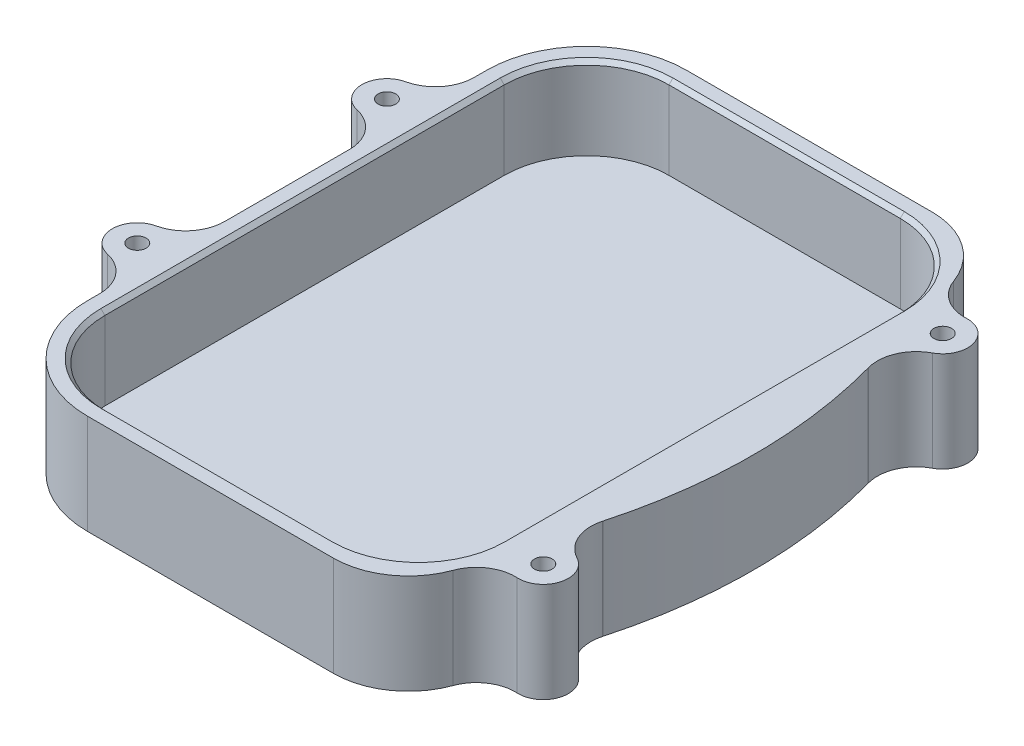
SolidWorks part; units mm, degrees
ref_plane "Front Plane" through (0, 0, 0) normal (0, 0, 1) x (1, 0, 0)
ref_plane "Top Plane" through (0, 0, 0) normal (0, 1, 0) x (1, 0, 0)
ref_plane "Right Plane" through (0, 0, 0) normal (1, 0, 0) x (0, 0, -1)
sketch "Sketch1" plane through (0, 0, 0) normal (0, 1, 0) x (1, 0, 0)
  line L1 (-68.58, 76.2) -> (68.58, 76.2)
  line L2 (-68.58, 76.2) -> (-68.58, -76.2)
  line L3 (-68.58, -76.2) -> (68.58, -76.2)
  line L4 (68.58, 76.2) -> (68.58, -76.2)
  line L5 (-68.58, 76.2) -> (68.58, -76.2) construction
  line L6 (-68.58, -76.2) -> (68.58, 76.2) construction
  point P0 (0, 0)
  dimension "D1" = 137.16
  dimension "D2" = 152.4
extrude "Boss-Extrude2" add sketch "Sketch1" against normal blind 25.4
sketch "Sketch2" plane through (0, 0, 0) normal (0, 1, 0) x (1, 0, 0)
  line L0 (61.1717, -50.8) -> (61.1717, 50.8) construction
  line L1 (-61.1717, 31.75) -> (-61.1717, -31.75) construction
  line L2 (-61.1717, 0) -> (61.1717, 0) construction
  circle A0 centre (-61.1717, 31.75) radius 2.2479
  circle A1 centre (-61.1717, -31.75) radius 2.2479
  circle A2 centre (61.1717, 50.8) radius 2.2479
  circle A3 centre (61.1717, -50.8) radius 2.2479
  point P8 (61.1717, 0)
  point P11 (0, 0)
  dimension "D2" = 4.4958
  dimension "D1" = 122.3433
  dimension "D3" = 101.6
  dimension "D4" = 63.5
sketch "Sketch3" plane through (0, 0, 0) normal (0, 1, 0) x (1, 0, 0)
  line L0 (-54.8217, 0) -> (-54.8217, -76.2) construction
  line L1 (68.58, -76.2) -> (68.58, 76.2) construction
  line L2 (-68.58, -76.2) -> (68.58, -76.2) construction
  line L3 (68.58, 0) -> (59.2627, -33.8209)
  line L4 (-61.1717, 0) -> (61.1717, 0) construction
  line L5 (-68.58, -76.2) -> (68.58, -76.2) construction
  line L6 (-54.8217, -47.6123) -> (-54.8217, -76.2)
  line L7 (50.8368, -64.4061) -> (47.5877, -76.2)
  line L8 (-54.8217, -15.8877) -> (-54.8217, 0)
  line L9 (-54.8217, 0) -> (-68.58, 0)
  line L10 (-68.58, 76.2) -> (-68.58, -76.2) construction
  line L11 (-68.58, 0) -> (-68.58, -76.2)
  line L12 (-68.58, -76.2) -> (-54.8217, -76.2)
  line L13 (47.5877, -76.2) -> (68.58, -76.2)
  line L14 (68.58, -76.2) -> (68.58, 0)
  arc A1 (60.8652, -57.1426) -> (64.1565, -45.1953) centre (61.1717, -50.8) ccw
  arc A2 (59.2627, -33.8209) -> (64.1565, -45.1953) centre (68.8129, -36.4519) ccw
  arc A3 (60.8652, -57.1426) -> (50.8368, -64.4061) centre (60.387, -67.0371) ccw
  arc A4 (-62.5607, -25.5538) -> (-62.5607, -37.9462) centre (-61.1717, -31.75) ccw
  arc A5 (-62.5607, -25.5538) -> (-54.8217, -15.8877) centre (-64.7277, -15.8877) ccw
  arc A6 (-54.8217, -47.6123) -> (-62.5607, -37.9462) centre (-64.7277, -47.6123) ccw
  dimension "D3" = 12.7
  dimension "D4" = 19.812
  dimension "D5" = 19.812
  dimension "D1" = 12.7
  dimension "D2" = 6.35
extrude "Cut-Extrude1" cut sketch "Sketch3" against normal up to surface (25.4 mm away) up to face at (0, -25.4, 0)
mirror "Mirror1" about plane through (-54.8217, -104.4387, 0) normal (0, 0, -1) of "Cut-Extrude1"
extrude "Cut-Extrude2" cut sketch "Sketch2" against normal up to surface (25.4 mm away) up to face at (2.6053, -25.4, 0)
fillet "Fillet2" radius 25.4 2 edges at (-54.8217, -12.7, -76.2) (-54.8217, -12.7, 76.2)
fillet "Fillet3" radius 19.05 2 edges at (47.5877, -12.7, 76.2) (47.5877, -12.7, -76.2)
fillet "Fillet4" radius 127 1 edges at (68.58, -12.7, 0)
sketch "Sketch4" plane through (0, 0, 0) normal (0, 1, 0) x (1, 0, 0)
  line L0 (-50.3767, 50.8) -> (-50.3767, -50.8)
  line L1 (-29.4217, 71.755) -> (29.4217, 71.755)
  line L2 (-29.4217, -71.755) -> (29.4217, -71.755)
  line L3 (0, 71.755) -> (0, -71.755) construction
  line L4 (50.3767, 50.8) -> (50.3767, -50.8)
  line L14 (54.9773, -32.6403) -> (55.0022, -32.5501)
  line L15 (55.0022, 32.5501) -> (54.9773, 32.6403)
  line L16 (33.1713, 71.755) -> (-29.4217, 71.755)
  line L17 (-50.3767, 50.8) -> (-50.3767, 47.6123)
  line L18 (-50.3767, 15.8877) -> (-50.3767, -15.8877)
  line L19 (-50.3767, -47.6123) -> (-50.3767, -50.8)
  line L20 (-29.4217, -71.755) -> (33.1713, -71.755)
  arc A0 (50.3767, -50.8) -> (29.4217, -71.755) centre (29.4217, -50.8) cw
  arc A1 (29.4217, 71.755) -> (50.3767, 50.8) centre (29.4217, 50.8) cw
  arc A34 (55.0022, -32.5501) -> (55.0022, 32.5501) centre (-63.1512, 0) ccw
  arc A35 (62.0671, 49.1186) -> (54.9773, 32.6403) centre (68.8129, 36.4519) ccw
  arc A36 (62.0671, 49.1186) -> (61.0797, 52.7028) centre (61.1717, 50.8) ccw
  arc A37 (46.8985, 62.1369) -> (61.0797, 52.7028) centre (60.387, 67.0371) ccw
  arc A38 (46.8985, 62.1369) -> (33.1713, 71.755) centre (33.1713, 57.15) ccw
  arc A39 (-29.4217, 71.755) -> (-50.3767, 50.8) centre (-29.4217, 50.8) ccw
  arc A40 (-61.5884, 33.6089) -> (-50.3767, 47.6123) centre (-64.7277, 47.6123) ccw
  arc A41 (-61.5884, 33.6089) -> (-61.5884, 29.8911) centre (-61.1717, 31.75) ccw
  arc A42 (-50.3767, 15.8877) -> (-61.5884, 29.8911) centre (-64.7277, 15.8877) ccw
  arc A43 (-61.5884, -29.8911) -> (-50.3767, -15.8877) centre (-64.7277, -15.8877) ccw
  arc A44 (-61.5884, -29.8911) -> (-61.5884, -33.6089) centre (-61.1717, -31.75) ccw
  arc A45 (-50.3767, -47.6123) -> (-61.5884, -33.6089) centre (-64.7277, -47.6123) ccw
  arc A46 (-50.3767, -50.8) -> (-29.4217, -71.755) centre (-29.4217, -50.8) ccw
  arc A47 (33.1713, -71.755) -> (46.8985, -62.1369) centre (33.1713, -57.15) ccw
  arc A48 (61.0797, -52.7028) -> (46.8985, -62.1369) centre (60.387, -67.0371) ccw
  arc A49 (61.0797, -52.7028) -> (62.0671, -49.1186) centre (61.1717, -50.8) ccw
  arc A50 (54.9773, -32.6403) -> (62.0671, -49.1186) centre (68.8129, -36.4519) ccw
  arc A56 (-29.4217, 71.755) -> (-50.3767, 50.8) centre (-29.4217, 50.8) ccw
  arc A63 (-50.3767, -50.8) -> (-29.4217, -71.755) centre (-29.4217, -50.8) ccw
  dimension "D1" = 4.445
extrude "Cut-Extrude3" cut sketch "Sketch4" against normal offset from surface (20.955 mm away) 4.445 up to face at (61.1717, -25.4, 53.0479)
chamfer "Chamfer1" distance 1.016 angle 45 8 edges at (0, 0, 71.755) (44.2391, 0, 65.6174) (-44.2391, 0, 65.6174) (50.3767, 0, 0) (-50.3767, 0, 0) (44.2391, 0, -65.6174) (-44.2391, 0, -65.6174) (0, 0, -71.755)
